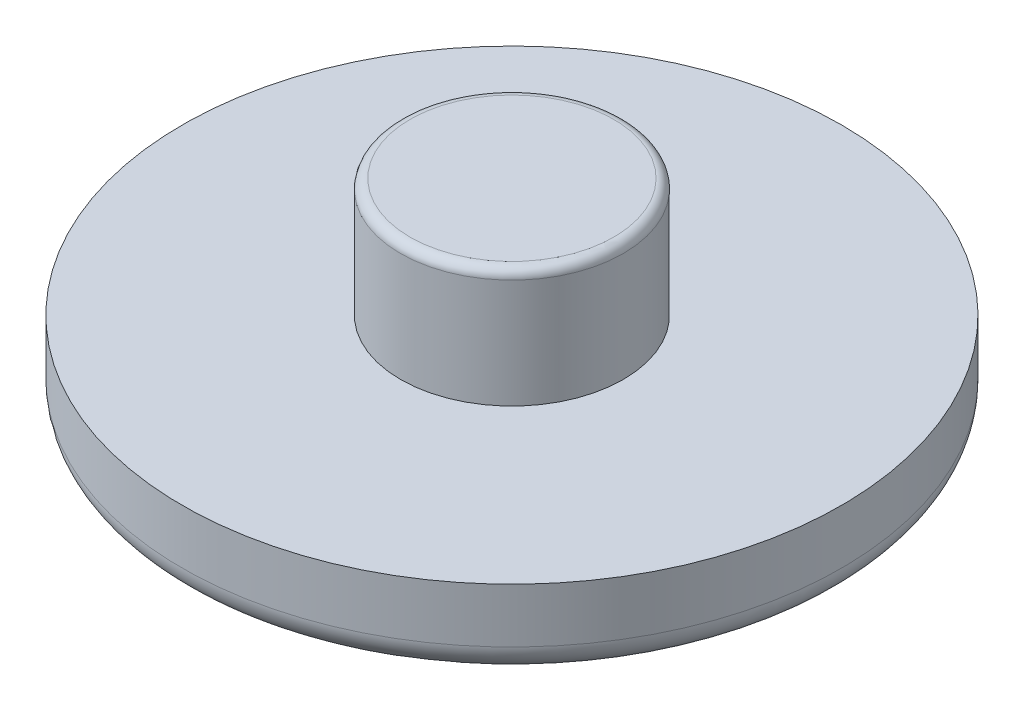
SolidWorks part; units mm, degrees
ref_plane "Front Plane" through (0, 0, 0) normal (0, 0, 1) x (1, 0, 0)
ref_plane "Top Plane" through (0, 0, 0) normal (0, 1, 0) x (1, 0, 0)
ref_plane "Right Plane" through (0, 0, 0) normal (1, 0, 0) x (0, 0, -1)
sketch "Sketch1" plane through (0, 0, 0) normal (0, 1, 0) x (1, 0, 0)
  circle A1 centre (0, 0) radius 17.653
extrude "Boss-Extrude1" add sketch "Sketch1" along normal blind 7.62
sketch "Sketch2" plane through (0, 7.62, 0) normal (0, 1, 0) x (1, 0, 0)
  circle A0 centre (0, 0) radius 5.969
  dimension "D1" = 11.938
extrude "Boss-Extrude2" add sketch "Sketch2" along normal blind 6.35 contours A0
chamfer "Chamfer1" distance 10 angle 20 1 edges at (0, 0, 17.653)
fillet "Fillet1" radius 1.524 2 edges at (0, 0, 7.653) (0, 3.6397, 17.653)
fillet "Fillet2" radius 0.508 1 edges at (0, 13.97, 5.969)
